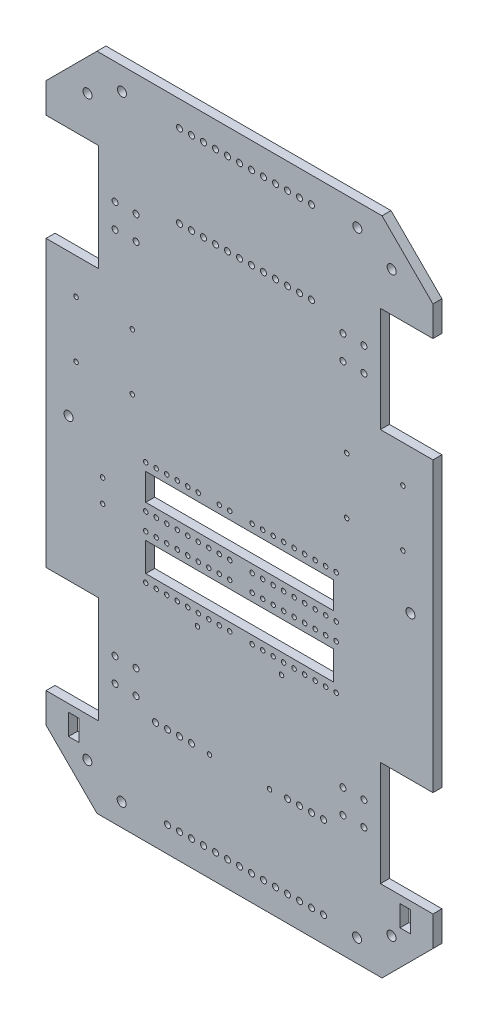
SolidWorks part; units mm, degrees
material "PE High Density"
ref_plane "Front Plane" through (0, 0, 0) normal (0, 0, 1) x (1, 0, 0)
ref_plane "Top Plane" through (0, 0, 0) normal (0, 1, 0) x (1, 0, 0)
ref_plane "Right Plane" through (0, 0, 0) normal (1, 0, 0) x (0, 0, -1)
sketch "Sketch2" plane through (0, 0, 0) normal (0, 0, 1) x (1, 0, 0)
  line L0 (0, 103.7752) -> (0, -103.7752) construction
  line L1 (-175.5058, 7.5589) -> (175.5058, 7.5589) construction
  line L2 (-95, 227.5589) -> (95, 227.5589)
  line L3 (95, 227.5589) -> (128.9411, 193.6177)
  line L4 (-95, 227.5589) -> (-128.9411, 193.6177)
  line L5 (-128.9411, 193.6177) -> (-128.9411, 173.6177)
  line L6 (128.9411, 193.6177) -> (128.9411, 173.6177)
  line L7 (-128.9411, 173.6177) -> (-93.9411, 173.6177)
  line L8 (128.9411, 173.6177) -> (93.9411, 173.6177)
  line L9 (93.9411, 173.6177) -> (93.9411, 103.6177)
  line L10 (-93.9411, 173.6177) -> (-93.9411, 102.5589)
  line L11 (-93.9411, 102.5589) -> (-128.9411, 102.5589)
  line L12 (-128.9411, 102.5589) -> (-128.9411, -87.4411)
  line L13 (93.9411, 103.6177) -> (128.9411, 103.6177)
  line L14 (128.9411, 103.6177) -> (128.9411, -88.5)
  line L15 (-62.5, -57.7719) -> (-62.5, -38.615)
  line L16 (-81.5, 200.5589) -> (81.5, 200.5589)
  line L17 (93.9411, -88.5) -> (128.9411, -88.5)
  line L18 (-93.9411, -87.4411) -> (-128.9411, -87.4411)
  line L19 (-93.9411, -158.5) -> (-93.9411, -87.4411)
  line L20 (93.9411, -158.5) -> (93.9411, -88.5)
  line L21 (128.9411, -158.5) -> (93.9411, -158.5)
  line L22 (-128.9411, -158.5) -> (-93.9411, -158.5)
  line L23 (128.9411, -178.5) -> (128.9411, -158.5)
  line L24 (-128.9411, -178.5) -> (-128.9411, -158.5)
  line L25 (-95, -212.4411) -> (-128.9411, -178.5)
  line L26 (95, -212.4411) -> (128.9411, -178.5)
  line L27 (-95, -212.4411) -> (95, -212.4411)
  line L28 (-40, 90.4971) -> (40, 90.4971)
  line L29 (-40, 90.4971) -> (-40, 20.4971)
  line L30 (-40, 20.4971) -> (40, 20.4971)
  line L31 (40, 90.4971) -> (40, 20.4971)
  line L32 (-40, 90.4971) -> (40, 20.4971) construction
  line L33 (-40, 20.4971) -> (40, 90.4971) construction
  line L34 (-81.5, 200.5589) -> (-81.5, 165.5589)
  line L35 (-81.5, 165.5589) -> (81.5, 165.5589)
  line L36 (81.5, 200.5589) -> (81.5, 165.5589)
  line L37 (-81.5, 200.5589) -> (81.5, 165.5589) construction
  line L38 (-81.5, 165.5589) -> (81.5, 200.5589) construction
  line L39 (-81.5, -150.4411) -> (81.5, -185.4411) construction
  line L40 (-81.5, -185.4411) -> (81.5, -150.4411) construction
  line L41 (81.5, -185.4411) -> (81.5, -150.4411)
  line L42 (-81.5, -150.4411) -> (81.5, -150.4411)
  line L43 (-81.5, -185.4411) -> (-81.5, -150.4411)
  line L44 (-81.5, -185.4411) -> (81.5, -185.4411)
  line L45 (62.5, -57.7719) -> (-62.5, -57.7719)
  line L46 (62.5, -38.615) -> (62.5, -57.7719)
  line L47 (-62.5, -38.615) -> (62.5, -38.615)
  line L48 (62.5, 1.2281) -> (-62.5, 1.2281)
  line L49 (62.5, -16.601) -> (62.5, 1.2281)
  line L50 (-62.5, -16.601) -> (62.5, -16.601)
  line L51 (-62.5, 1.2281) -> (-62.5, -16.601)
  line L52 (-113.9411, -163.5) -> (-113.9411, -177.5)
  line L53 (106.9411, -163.5) -> (113.9411, -163.5)
  line L54 (106.9411, -163.5) -> (106.9411, -177.5)
  line L55 (106.9411, -177.5) -> (113.9411, -177.5)
  line L56 (113.9411, -163.5) -> (113.9411, -177.5)
  line L57 (-106.9411, -177.5) -> (-113.9411, -177.5)
  line L58 (-106.9411, -163.5) -> (-106.9411, -177.5)
  line L59 (-106.9411, -163.5) -> (-113.9411, -163.5)
  circle A0 centre (-82.9411, 146.6177) radius 2
  circle A1 centre (-68.9411, 146.6177) radius 2
  circle A4 centre (-82.9411, 130.6177) radius 2
  circle A5 centre (-68.9411, 130.6177) radius 2
  circle A6 centre (68.9411, 130.6177) radius 2
  circle A7 centre (82.9411, 130.6177) radius 2
  circle A8 centre (68.9411, 146.6177) radius 2
  circle A9 centre (82.9411, 146.6177) radius 2
  circle A10 centre (82.9411, -131.5) radius 2
  circle A11 centre (68.9411, -131.5) radius 2
  circle A12 centre (82.9411, -115.5) radius 2
  circle A13 centre (68.9411, -115.5) radius 2
  circle A14 centre (-68.9411, -115.5) radius 2
  circle A15 centre (-82.9411, -115.5) radius 2
  circle A16 centre (-68.9411, -131.5) radius 2
  circle A17 centre (-82.9411, -131.5) radius 2
  circle A18 centre (108.9411, 41.306) radius 1.5
  circle A19 centre (71.4411, 41.306) radius 1.5
  circle A20 centre (108.9411, 78.806) radius 1.5
  circle A21 centre (71.4411, 78.806) radius 1.5
  circle A22 centre (-71.4411, 78.806) radius 1.5
  circle A23 centre (-108.9411, 78.806) radius 1.5
  circle A24 centre (-71.4411, 41.306) radius 1.5
  circle A25 centre (-108.9411, 41.306) radius 1.5
  circle A26 centre (0, 210.5589) radius 2
  circle A27 centre (8, 210.5589) radius 2
  circle A28 centre (16, 210.5589) radius 2
  circle A29 centre (24, 210.5589) radius 2
  circle A30 centre (32, 210.5589) radius 2
  circle A31 centre (40, 210.5589) radius 2
  circle A32 centre (48, 210.5589) radius 2
  circle A36 centre (-8, 210.5589) radius 2
  circle A37 centre (-16, 210.5589) radius 2
  circle A38 centre (-24, 210.5589) radius 2
  circle A39 centre (-32, 210.5589) radius 2
  circle A40 centre (-40, 210.5589) radius 2
  circle A49 centre (-40, 155.5589) radius 2
  circle A50 centre (-32, 155.5589) radius 2
  circle A51 centre (-24, 155.5589) radius 2
  circle A52 centre (-16, 155.5589) radius 2
  circle A53 centre (-8, 155.5589) radius 2
  circle A57 centre (48, 155.5589) radius 2
  circle A58 centre (40, 155.5589) radius 2
  circle A59 centre (32, 155.5589) radius 2
  circle A60 centre (24, 155.5589) radius 2
  circle A61 centre (16, 155.5589) radius 2
  circle A62 centre (8, 155.5589) radius 2
  circle A63 centre (0, 155.5589) radius 2
  circle A68 centre (32, -140.4411) radius 2
  circle A69 centre (40, -140.4411) radius 2
  circle A70 centre (48, -140.4411) radius 2
  circle A71 centre (56, -140.4411) radius 2
  circle A77 centre (-32, -140.4411) radius 2
  circle A78 centre (-40, -140.4411) radius 2
  circle A79 centre (-48, -140.4411) radius 2
  circle A80 centre (-56, -140.4411) radius 2
  circle A86 centre (-48, -195.4411) radius 2
  circle A87 centre (-40, -195.4411) radius 2
  circle A88 centre (-32, -195.4411) radius 2
  circle A89 centre (-24, -195.4411) radius 2
  circle A90 centre (-16, -195.4411) radius 2
  circle A91 centre (-8, -195.4411) radius 2
  circle A94 centre (56, -195.4411) radius 2
  circle A95 centre (48, -195.4411) radius 2
  circle A96 centre (40, -195.4411) radius 2
  circle A97 centre (32, -195.4411) radius 2
  circle A98 centre (24, -195.4411) radius 2
  circle A99 centre (16, -195.4411) radius 2
  circle A100 centre (8, -195.4411) radius 2
  circle A101 centre (0, -195.4411) radius 2
  circle A102 centre (-20, -140.9472) radius 1.5
  circle A103 centre (64.414, -63.0631) radius 1.5
  circle A104 centre (57.414, -63.0631) radius 1.5
  circle A105 centre (50.414, -63.0631) radius 1.5
  circle A106 centre (43.414, -63.0631) radius 1.5
  circle A107 centre (36.414, -63.0631) radius 1.5
  circle A108 centre (29.414, -63.0631) radius 1.5
  circle A109 centre (28, -70.9472) radius 1.5
  circle A110 centre (22.414, -63.0631) radius 1.5
  circle A111 centre (15.414, -63.0631) radius 1.5
  circle A112 centre (8.414, -63.0631) radius 1.5
  circle A113 centre (-28, -70.9472) radius 1.5
  circle A114 centre (-6.5, -63.0631) radius 1.5
  circle A115 centre (-13.5, -63.0631) radius 1.5
  circle A116 centre (-20.5, -63.0631) radius 1.5
  circle A117 centre (-27.5, -63.0631) radius 1.5
  circle A118 centre (-34.5, -63.0631) radius 1.5
  circle A119 centre (-41.5, -63.0631) radius 1.5
  circle A120 centre (-48.5, -63.0631) radius 1.5
  circle A121 centre (-55.5, -63.0631) radius 1.5
  circle A122 centre (-62.5, -63.0631) radius 1.5
  circle A123 centre (64.414, -33.3238) radius 1.5
  circle A124 centre (57.414, -33.3238) radius 1.5
  circle A125 centre (50.414, -33.3238) radius 1.5
  circle A126 centre (43.414, -33.3238) radius 1.5
  circle A127 centre (36.414, -33.3238) radius 1.5
  circle A128 centre (29.414, -33.3238) radius 1.5
  circle A129 centre (22.414, -33.3238) radius 1.5
  circle A130 centre (8.414, -33.3238) radius 1.5
  circle A131 centre (15.414, -33.3238) radius 1.5
  circle A132 centre (-6.5, -33.3238) radius 1.5
  circle A133 centre (-13.5, -33.3238) radius 1.5
  circle A134 centre (-20.5, -33.3238) radius 1.5
  circle A135 centre (-27.5, -33.3238) radius 1.5
  circle A136 centre (-34.5, -33.3238) radius 1.5
  circle A137 centre (-41.5, -33.3238) radius 1.5
  circle A138 centre (-48.5, -33.3238) radius 1.5
  circle A139 centre (-55.5, -33.3238) radius 1.5
  circle A140 centre (-62.5, -33.3238) radius 1.5
  circle A141 centre (-62.5, -21.8921) radius 1.5
  circle A142 centre (-55.5, -21.8921) radius 1.5
  circle A143 centre (-48.5, -21.8921) radius 1.5
  circle A144 centre (-41.5, -21.8921) radius 1.5
  circle A145 centre (-34.5, -21.8921) radius 1.5
  circle A146 centre (-27.5, -21.8921) radius 1.5
  circle A147 centre (-20.5, -21.8921) radius 1.5
  circle A148 centre (-13.5, -21.8921) radius 1.5
  circle A149 centre (8.414, -21.8921) radius 1.5
  circle A150 centre (-6.5, -21.8921) radius 1.5
  circle A151 centre (15.414, -21.8921) radius 1.5
  circle A152 centre (22.414, -21.8921) radius 1.5
  circle A153 centre (29.414, -21.8921) radius 1.5
  circle A154 centre (36.414, -21.8921) radius 1.5
  circle A155 centre (43.414, -21.8921) radius 1.5
  circle A156 centre (50.414, -21.8921) radius 1.5
  circle A157 centre (64.414, -21.8921) radius 1.5
  circle A158 centre (57.414, -21.8921) radius 1.5
  circle A159 centre (64.414, 6.5193) radius 1.5
  circle A160 centre (57.414, 6.5193) radius 1.5
  circle A161 centre (50.414, 6.5193) radius 1.5
  circle A162 centre (43.414, 6.5193) radius 1.5
  circle A163 centre (36.414, 6.5193) radius 1.5
  circle A164 centre (29.414, 6.5193) radius 1.5
  circle A165 centre (22.414, 6.5193) radius 1.5
  circle A166 centre (15.414, 6.5193) radius 1.5
  circle A167 centre (8.414, 6.5193) radius 1.5
  circle A168 centre (-13.5, 6.5193) radius 1.5
  circle A169 centre (-6.5, 6.5193) radius 1.5
  circle A170 centre (-27.5, 6.5193) radius 1.5
  circle A171 centre (-41.5, 6.5193) radius 1.5
  circle A172 centre (-34.5, 6.5193) radius 1.5
  circle A173 centre (-48.5, 6.5193) radius 1.5
  circle A174 centre (-55.5, 6.5193) radius 1.5
  circle A175 centre (-62.5, 6.5193) radius 1.5
  circle A176 centre (-91.2472, -31.8324) radius 1.5
  circle A177 centre (-91.2472, -16.6506) radius 1.5
  circle A178 centre (20, -140.9472) radius 1.5
  circle A179 centre (72, 210.5589) radius 2 [skipped]
  circle A180 centre (64, 210.5589) radius 2 [skipped]
  circle A181 centre (56, 210.5589) radius 2 [skipped]
  circle A182 centre (-113.9411, 7.5589) radius 3
  circle A183 centre (113.9411, 7.5589) radius 3
  circle A184 centre (-101.294, 200.0517) radius 3
  circle A185 centre (101.4339, 199.9117) radius 3
  circle A186 centre (101.294, -184.9339) radius 3
  circle A187 centre (-101.4339, -184.794) radius 3
  circle A188 centre (-78.554, -197.4411) radius 3
  circle A189 centre (78.346, -197.4411) radius 3
  circle A190 centre (78.554, 212.5589) radius 3
  circle A191 centre (-78.346, 212.5589) radius 3
  point P4 (0, 0)
  point P8 (0, 7.5589)
  point P11 (0, 227.5589)
  point P59 (128.9411, 7.5589)
  point P61 (-128.9411, 7.5589)
  point P70 (0, -212.4411)
  point P83 (0, 55.4971)
  point P88 (0, 183.0589)
  point P171 (0, 138.5589)
  point P254 (0, -167.9411)
  dimension "D9" = 4
  dimension "D10" = 4
  dimension "D11" = 14
  dimension "D12" = 4
  dimension "D13" = 4
  dimension "D15" = 37.5
  dimension "D16" = 14
  dimension "D17" = 16
  dimension "D18" = 11
  dimension "D19" = 37.5
  dimension "D20" = 20
  dimension "D21" = 20
  dimension "D22" = 80
  dimension "D27" = 10
  dimension "D28" = 4
  dimension "D33" = 3
  dimension "D34" = 40
  dimension "D35" = 7
  dimension "D39" = 70
  dimension "D40" = 20
  dimension "D47" = 15
  dimension "D48" = 6
  dimension "D1" = 220
  dimension "D2" = 190
  dimension "D3" = 48
  dimension "D4" = 48
  dimension "D5" = 20
  dimension "D6" = 35
  dimension "D7" = 35
  dimension "D8" = 70
  dimension "D14" = 16
  dimension "D23" = 70
  dimension "D24" = 163
  dimension "D25" = 35
  dimension "D26" = 27
  dimension "D30" = 17.8291
  dimension "D31" = 56
  dimension "D32" = 70
  dimension "D36" = 14
  dimension "D37" = 5
  dimension "D38" = 15
  dimension "D41" = 45
  dimension "D42" = 45
  dimension "D43" = 45
  dimension "D44" = 20
  dimension "D45" = 190
  dimension "D46" = 192.1177
  dimension "D29" = 10
extrude "Boss-Extrude1" add sketch "Sketch2" along normal blind 6
sketch "Sketch3" plane through (0, 0, 6) normal (0, 0, 1) x (1, 0, 0)
  line L1 (-81.5, 200.5589) -> (81.5, 200.5589)
  line L2 (-81.5, 200.5589) -> (-81.5, 165.5589)
  line L3 (-81.5, 165.5589) -> (81.5, 165.5589)
  line L4 (81.5, 200.5589) -> (81.5, 165.5589)
  line L5 (-40, 90.4971) -> (40, 90.4971)
  line L6 (-40, 90.4971) -> (-40, 20.4971)
  line L7 (-40, 20.4971) -> (40, 20.4971)
  line L8 (40, 90.4971) -> (40, 20.4971)
  line L9 (-81.5, -150.4411) -> (81.5, -150.4411)
  line L10 (-81.5, -150.4411) -> (-81.5, -185.4411)
  line L11 (-81.5, -185.4411) -> (81.5, -185.4411)
  line L12 (81.5, -150.4411) -> (81.5, -185.4411)
extrude "Boss-Extrude2" add sketch "Sketch3" against normal blind 3
